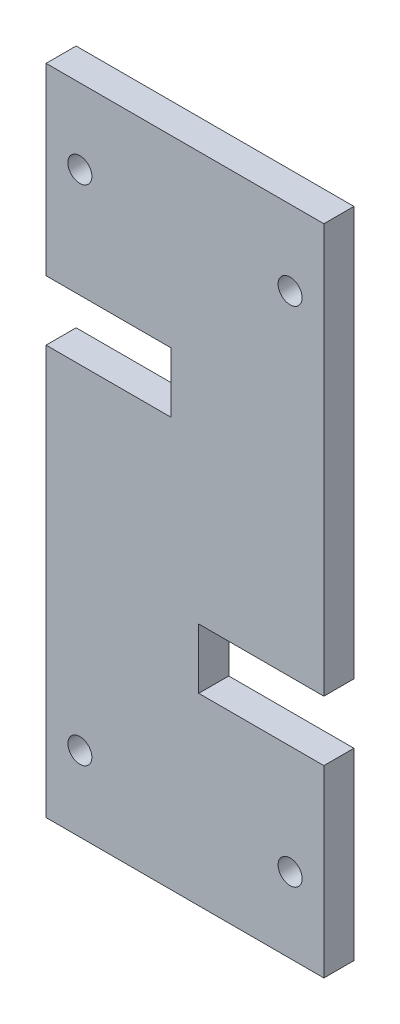
SolidWorks part; units mm, degrees
material "Thornel Mat VMA"
ref_plane "前视基准面" through (0, 0, 0) normal (0, 0, 1) x (1, 0, 0)
ref_plane "上视基准面" through (0, 0, 0) normal (0, 1, 0) x (1, 0, 0)
ref_plane "右视基准面" through (0, 0, 0) normal (1, 0, 0) x (0, 0, -1)
sketch "草图1" plane through (0, 0, 0) normal (0, 0, 1) x (1, 0, 0)
  line L0 (0, 45.4593) -> (0, -49.1687) construction
  line L1 (-32.3342, 0) -> (27.8756, 0) construction
  line L3 (-18.5, 43.5) -> (18.5, 43.5)
  line L4 (-18.5, 43.5) -> (-18.5, -43.5)
  line L5 (-18.5, -43.5) -> (18.5, -43.5)
  line L6 (18.5, 43.5) -> (18.5, -43.5)
  line L7 (-18.5, 43.5) -> (18.5, -43.5) construction
  line L8 (-18.5, -43.5) -> (18.5, 43.5) construction
  circle A0 centre (-14, 33.5) radius 1.6
  circle A1 centre (14, 33.5) radius 1.6
  circle A2 centre (-14, -33.5) radius 1.6
  circle A3 centre (14, -33.5) radius 1.6
  point P15 (0, 0)
  dimension "D1" = 3.2
  dimension "D2" = 67
  dimension "D3" = 28
  dimension "D4" = 10
  dimension "D5" = 4.5
extrude "凸台-拉伸1" add sketch "草图1" along normal blind 4
sketch "草图2" plane through (0, 0, 4) normal (0, 0, 1) x (1, 0, 0)
  line L0 (-43.9732, 0) -> (45.272, 0) construction
  line L1 (0, 47.164) -> (0, -50.0204) construction
  line L2 (-18.5, 43.5) -> (-18.5, -43.5) construction
  line L3 (-18.5, 19) -> (-1.83, 19)
  line L4 (-18.5, 19) -> (-18.5, 11)
  line L5 (-18.5, 11) -> (-1.83, 11)
  line L6 (-1.83, 19) -> (-1.83, 11)
  line L7 (18.5, -43.5) -> (18.5, 43.5) construction
  line L8 (18.5, -11) -> (1.83, -11)
  line L9 (18.5, -11) -> (18.5, -19)
  line L10 (18.5, -19) -> (1.83, -19)
  line L11 (1.83, -11) -> (1.83, -19)
  dimension "D1" = 19
  dimension "D2" = 8
  dimension "D3" = 16.67
  dimension "D4" = 19
  dimension "D5" = 8
  dimension "D6" = 16.67
  dimension "D7" = 1.83
  dimension "D8" = 1.83
extrude "切除-拉伸1" cut sketch "草图2" against normal through all
sketch "草图3" plane through (0, -43.5, 0) normal (0, -1, 0) x (1, 0, 0)
  line L0 (0, 9.9189) -> (0, -27.01) construction
  line L1 (-18.5, 0) -> (18.5, 0) construction
  line L2 (-94.3015, 12.515) -> (-14.2135, -46.3485)
  line L3 (-81.3804, 34.895) -> (9.6409, -5.0315)
  line L4 (0, -27.01) -> (-86.6025, 22.99) construction
  circle A0 centre (0, -27.01) radius 24
  circle A1 centre (-86.6025, 22.99) radius 13
  point P1 (-1.8296, 0)
  dimension "D1" = 27.01
  dimension "D2" = 48
  dimension "D3" = 26
  dimension "D4" = 100
  dimension "D5" = 60
  dimension "D6" = 1.8296
